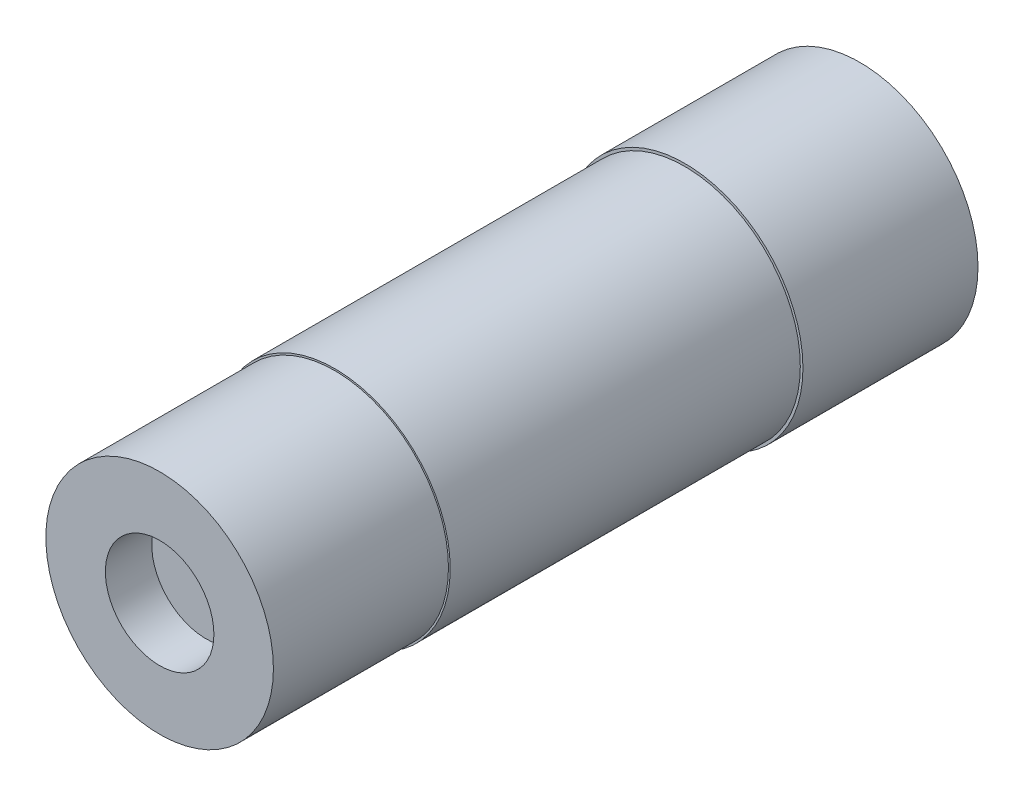
SolidWorks part; units mm, degrees
ref_plane "Front Plane" through (0, 0, 0) normal (0, 0, 1) x (1, 0, 0)
ref_plane "Top Plane" through (0, 0, 0) normal (0, 1, 0) x (1, 0, 0)
ref_plane "Right Plane" through (0, 0, 0) normal (1, 0, 0) x (0, 0, -1)
sketch "Sketch1" plane through (0, 0, 0) normal (0, 0, 1) x (1, 0, 0)
  circle A0 centre (0, 0) radius 6.75
  circle A1 centre (0, 0) radius 2.725
  dimension "D1" = 5.45
  dimension "D2" = 13.5
extrude "Boss-Extrude2" add sketch "Sketch1" along normal blind 10
sketch "Sketch2" plane through (0, 0, 10) normal (0, 0, 1) x (1, 0, 0)
  circle A0 centre (0, 0) radius 6.6
  dimension "D1" = 13.2
extrude "Boss-Extrude3" add sketch "Sketch2" along normal blind 30
sketch "Sketch3" plane through (0, 0, 40) normal (0, 0, 1) x (1, 0, 0)
  circle A0 centre (0, 0) radius 6.5
  circle A1 centre (0, 0) radius 6.5
  circle A2 centre (0, 0) radius 6.6 construction
  circle M1 centre (0, 0) radius 6.6
  dimension "D1" = 13
  dimension "D2" = 0.1
extrude "Cut-Extrude1" cut sketch "Sketch3" against normal blind 10 contours A0 M1
sketch "Sketch4" plane through (0, 0, 40) normal (0, 0, 1) x (1, 0, 0)
  circle A0 centre (0, 0) radius 3.1
  dimension "D1" = 6.2
extrude "Cut-Extrude3" cut sketch "Sketch4" against normal blind 2.65
